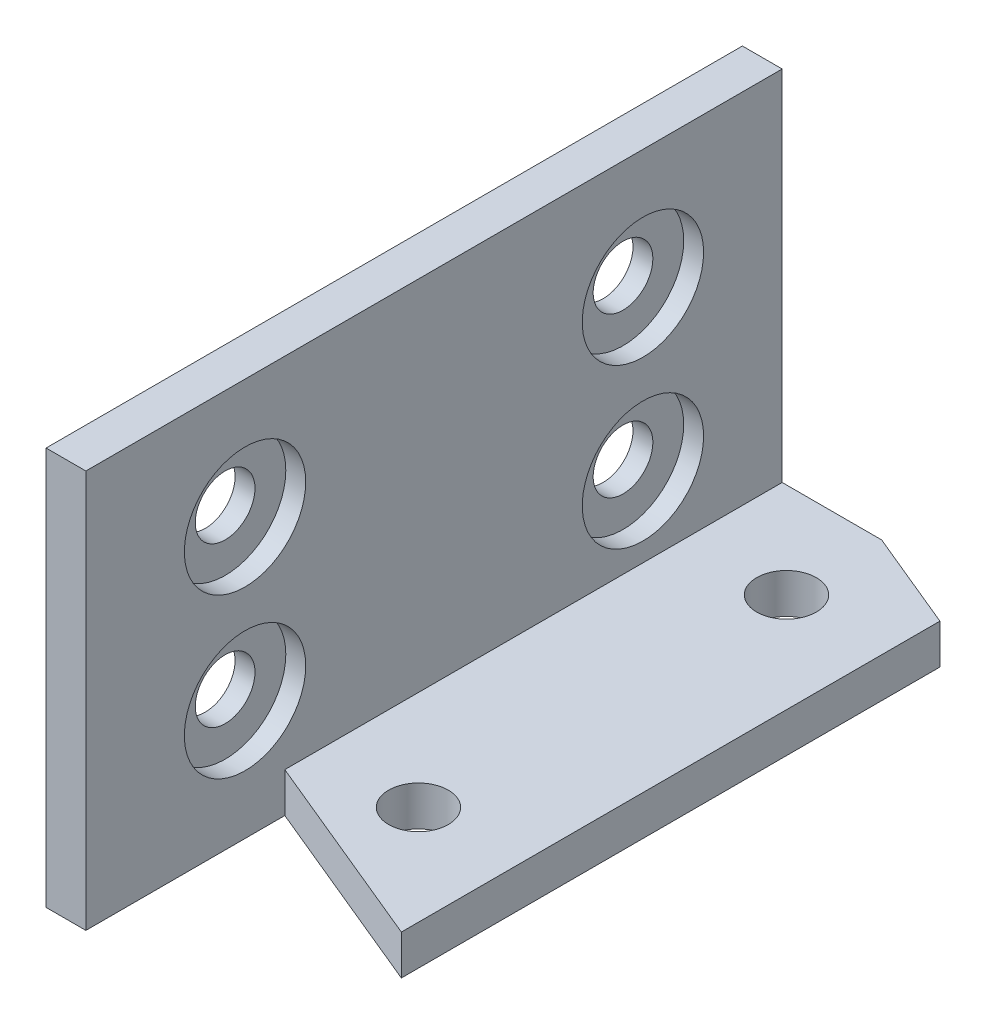
SolidWorks part; units mm, degrees
ref_plane "Front Plane" through (0, 0, 0) normal (0, 0, 1) x (1, 0, 0)
ref_plane "Top Plane" through (0, 0, 0) normal (0, 1, 0) x (1, 0, 0)
ref_plane "Right Plane" through (0, 0, 0) normal (1, 0, 0) x (0, 0, -1)
sketch "Sketch1" plane through (0, 0, 0) normal (1, 0, 0) x (0, 0, -1)
  line L1 (-17.5, -10) -> (17.5, -10)
  line L2 (-17.5, -10) -> (-17.5, 10)
  line L3 (-17.5, 10) -> (17.5, 10)
  line L4 (17.5, -10) -> (17.5, 10)
  line L5 (-17.5, -10) -> (17.5, 10) construction
  line L6 (-17.5, 10) -> (17.5, -10) construction
  point P0 (0, 0)
  dimension "D1" = 20
  dimension "D2" = 35
extrude "Boss-Extrude1" add sketch "Sketch1" along normal blind 2
sketch "Sketch3" plane through (2, 0, 0) normal (1, 0, 0) x (0, 0, -1)
  line L0 (17.5, -10) -> (17.5, 10) construction
  line L1 (-9.5, -4) -> (10.5, -4) construction
  line L2 (-9.5, -4) -> (-9.5, 4) construction
  line L3 (-9.5, 4) -> (10.5, 4) construction
  line L4 (10.5, -4) -> (10.5, 4) construction
  line L6 (-17.5, -10) -> (17.5, -10) construction
  circle A0 centre (10.5, 4) radius 1.5
  circle A1 centre (10.5, -4) radius 1.5
  circle A2 centre (-9.5, 4) radius 1.5
  circle A3 centre (-9.5, -4) radius 1.5
  dimension "D2" = 3
  dimension "D1" = 7
  dimension "D3" = 8
  dimension "D4" = 20
  dimension "D5" = 6
extrude "Cut-Extrude1" cut sketch "Sketch3" against normal up to surface (2 mm away) up to face at (0, 0, 0)
sketch "Sketch4" plane through (0, -10, 0) normal (0, -1, 0) x (1, 0, 0)
  line L7 (2, 7.5) -> (12, 11.6421)
  line L8 (2, 17.5) -> (2, -17.5) construction
  line L9 (12, 11.6421) -> (12, -15.4289)
  line L11 (2, -17.5) -> (2, 7.5)
  line L12 (2, 17.5) -> (0, 17.5) construction
  line L14 (2, -17.5) -> (7, -17.5)
  line L15 (7, -17.5) -> (12, -15.4289)
  point P6 (0, 0)
  dimension "D1" = 22.5
  dimension "D2" = 5
  dimension "D3" = 10
  dimension "D4" = 27.0711
extrude "Boss-Extrude2" add sketch "Sketch4" against normal blind 2
sketch "Sketch5" plane through (0, -8, 0) normal (0, 1, 0) x (1, 0, 0)
  line L0 (7, 12.7173) -> (7, -5.7827) construction
  line L1 (2, 17.5) -> (2, -17.5) construction
  line L2 (12, -11.6421) -> (2, -7.5) construction
  line L3 (2, -7.5) -> (2, 17.5) construction
  circle A0 centre (7, 12.7173) radius 1.5
  circle A1 centre (7, -5.7827) radius 1.5
  point P12 (15.1521, 9.8235)
  dimension "D1" = 3
  dimension "D2" = 18.5
  dimension "D3" = 3.5
  dimension "D4" = 5
extrude "Cut-Extrude2" cut sketch "Sketch5" against normal up to surface (2 mm away) up to face at (5, -10, 0.5305)
sketch "Sketch6" plane through (2, 0, 0) normal (1, 0, 0) x (0, 0, -1)
  circle A0 centre (-9.5, 4) radius 3.05
  circle A1 centre (-9.5, -4) radius 3.05
  circle A2 centre (10.5, -4) radius 3.05
  circle A3 centre (10.5, 4) radius 3.05
  dimension "D1" = 6.1
extrude "Cut-Extrude3" cut sketch "Sketch6" against normal blind 1
